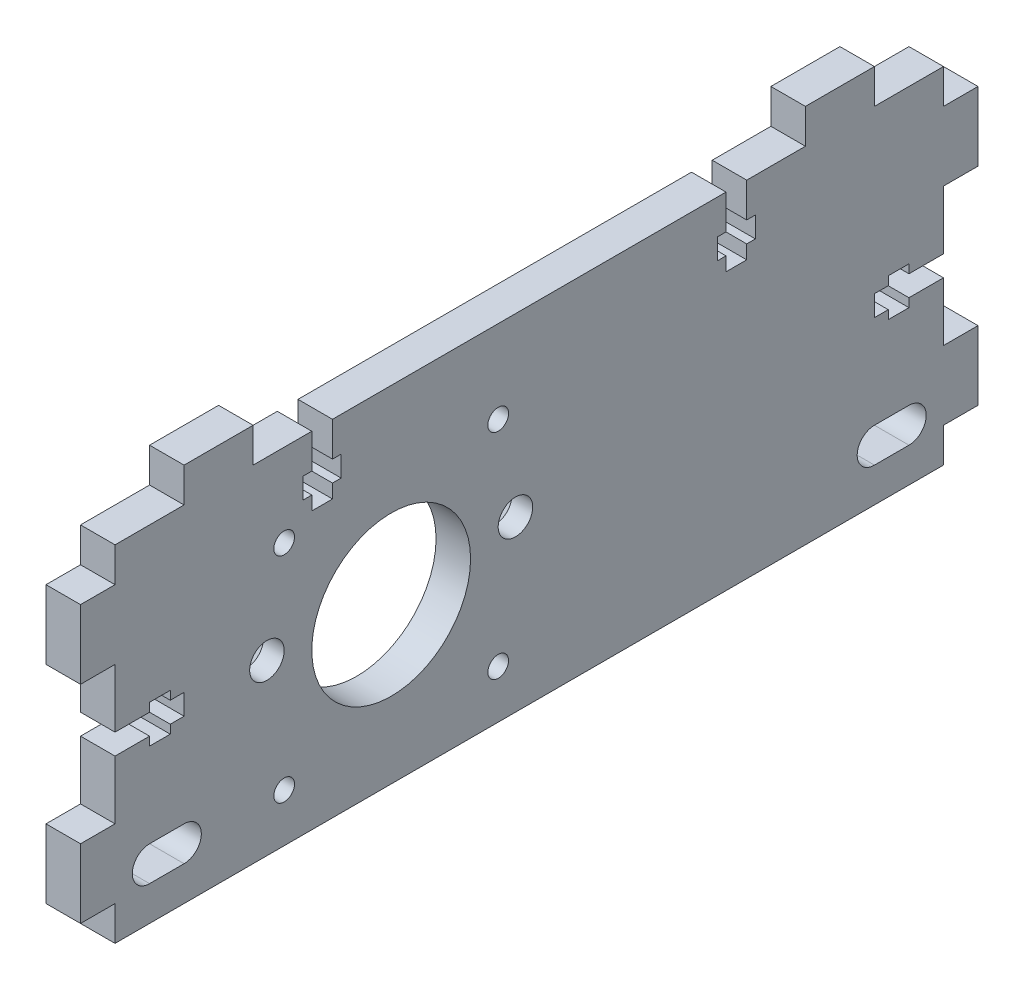
SolidWorks part; units mm, degrees
material "Maple"
ref_plane "Front Plane" through (0, 0, 0) normal (0, 0, 1) x (1, 0, 0)
ref_plane "Top Plane" through (0, 0, 0) normal (0, 1, 0) x (1, 0, 0)
ref_plane "Right Plane" through (0, 0, 0) normal (1, 0, 0) x (0, 0, -1)
sketch "Sketch1" plane through (0, 0, 0) normal (1, 0, 0) x (0, 0, -1)
  line L0 (-95.5, 38) -> (-64.5, 7) construction
  line L1 (-120, 50) -> (0, 50)
  line L2 (-120, 50) -> (-120, 0)
  line L3 (-120, 0) -> (0, 0)
  line L4 (0, 50) -> (0, 0)
  line L5 (-95.5, 38) -> (-64.5, 38) construction
  line L6 (-95.5, 38) -> (-95.5, 7) construction
  line L7 (-95.5, 7) -> (-64.5, 7) construction
  line L8 (-64.5, 38) -> (-64.5, 7) construction
  line L9 (-80, 22.5) -> (-80, 50) construction
  line L10 (-98, 24.5) -> (-80, 24.5) construction
  line L11 (-80, 24.5) -> (-62, 24.5) construction
  line L12 (-60, 50) -> (-60, 0) construction
  circle A0 centre (-95.5, 38) radius 1.5
  circle A1 centre (-64.5, 38) radius 1.5
  circle A2 centre (-64.5, 7) radius 1.5
  circle A3 centre (-95.5, 7) radius 1.5
  circle A4 centre (-80, 22.5) radius 11.5
  circle A5 centre (-98, 24.5) radius 2.5
  circle A6 centre (-62, 24.5) radius 2.5
  point P21 (-60, 50)
  dimension "D3" = 25.5
  dimension "D4" = 3
  dimension "D8" = 5
  dimension "D10" = 23
  dimension "D1" = 120
  dimension "D2" = 50
  dimension "D5" = 31
  dimension "D6" = 27.5
  dimension "D7" = 18
  dimension "D9" = 20
extrude "Boss-Extrude1" add sketch "Sketch1" along normal blind 5
chamfer "Chamfer1" distance 2 angle 45 2 edges at (0, 24.5, 95.5) (0, 24.5, 59.5)
sketch "Sketch2" plane through (5, 0, 0) normal (1, 0, 0) x (0, 0, -1)
  line L0 (-120, 50) -> (-120, 0) construction
  line L1 (-120, 5) -> (-125, 5)
  line L2 (-120, 5) -> (-120, 15)
  line L3 (-120, 15) -> (-125, 15)
  line L4 (-125, 5) -> (-125, 15)
  line L5 (-120, 45) -> (-125, 45)
  line L6 (-120, 45) -> (-120, 35)
  line L7 (-120, 35) -> (-125, 35)
  line L8 (-125, 45) -> (-125, 35)
  line L9 (0, 50) -> (-120, 50) construction
  line L10 (-110, 50) -> (-100, 50)
  line L11 (-110, 50) -> (-110, 55)
  line L12 (-110, 55) -> (-100, 55)
  line L13 (-100, 50) -> (-100, 55)
  line L14 (-60, 50) -> (-60, 0) construction
  line L15 (-120, 0) -> (0, 0) construction
  line L16 (-20, 50) -> (-20, 55)
  line L17 (-10, 55) -> (-20, 55)
  line L18 (-10, 50) -> (-10, 55)
  line L19 (-10, 50) -> (-20, 50)
  line L20 (5, 45) -> (5, 35)
  line L21 (0, 35) -> (5, 35)
  line L22 (0, 45) -> (0, 35)
  line L23 (0, 45) -> (5, 45)
  line L24 (5, 5) -> (5, 15)
  line L25 (0, 15) -> (5, 15)
  line L26 (0, 5) -> (0, 15)
  line L27 (0, 5) -> (5, 5)
  dimension "D1" = 5
  dimension "D2" = 10
  dimension "D3" = 10
  dimension "D4" = 10
  dimension "D5" = 10
  dimension "D6" = 5
  dimension "D7" = 5
extrude "Boss-Extrude2" add sketch "Sketch2" against normal up to surface (5 mm away) up to face at (0, 24.5, 93.5)
sketch "Sketch3" plane through (5, 0, 0) normal (1, 0, 0) x (0, 0, -1)
  line L0 (0, 26.5) -> (-5, 26.5)
  line L1 (-5, 26.5) -> (-5, 27.75)
  line L2 (-5, 27.75) -> (-8, 27.75)
  line L3 (-8, 27.75) -> (-8, 26.5)
  line L4 (-8, 26.5) -> (-10, 26.5)
  line L5 (-10, 26.5) -> (-10, 23.5)
  line L6 (-10, 23.5) -> (-8, 23.5)
  line L7 (-8, 23.5) -> (-8, 22.25)
  line L8 (-8, 22.25) -> (-5, 22.25)
  line L9 (-5, 22.25) -> (-5, 23.5)
  line L10 (-5, 23.5) -> (0, 23.5)
  line L11 (0, 23.5) -> (0, 26.5)
  line L12 (0, 15) -> (0, 35) construction
  line L13 (-60, 0) -> (-60, 50) construction
  line L14 (-120, 0) -> (0, 0) construction
  line L15 (-20, 50) -> (-100, 50) construction
  line L16 (-120, 23.5) -> (-120, 26.5)
  line L17 (-115, 23.5) -> (-120, 23.5)
  line L18 (-115, 22.25) -> (-115, 23.5)
  line L19 (-112, 22.25) -> (-115, 22.25)
  line L20 (-112, 23.5) -> (-112, 22.25)
  line L21 (-110, 23.5) -> (-112, 23.5)
  line L22 (-110, 26.5) -> (-110, 23.5)
  line L23 (-112, 26.5) -> (-110, 26.5)
  line L24 (-112, 27.75) -> (-112, 26.5)
  line L25 (-115, 27.75) -> (-112, 27.75)
  line L26 (-115, 26.5) -> (-115, 27.75)
  line L27 (-120, 26.5) -> (-115, 26.5)
  line L28 (-31.5, 50) -> (-31.5, 45)
  line L29 (-31.5, 45) -> (-32.75, 45)
  line L30 (-32.75, 45) -> (-32.75, 42)
  line L31 (-32.75, 42) -> (-31.5, 42)
  line L32 (-31.5, 42) -> (-31.5, 40)
  line L33 (-31.5, 40) -> (-28.5, 40)
  line L34 (-28.5, 40) -> (-28.5, 42)
  line L35 (-28.5, 42) -> (-27.25, 42)
  line L36 (-27.25, 42) -> (-27.25, 45)
  line L37 (-27.25, 45) -> (-28.5, 45)
  line L38 (-28.5, 45) -> (-28.5, 50)
  line L39 (-28.5, 50) -> (-31.5, 50)
  line L40 (-91.5, 50) -> (-88.5, 50)
  line L41 (-91.5, 45) -> (-91.5, 50)
  line L42 (-92.75, 45) -> (-91.5, 45)
  line L43 (-92.75, 42) -> (-92.75, 45)
  line L44 (-91.5, 42) -> (-92.75, 42)
  line L45 (-91.5, 40) -> (-91.5, 42)
  line L46 (-88.5, 40) -> (-91.5, 40)
  line L47 (-88.5, 42) -> (-88.5, 40)
  line L48 (-87.25, 42) -> (-88.5, 42)
  line L49 (-87.25, 45) -> (-87.25, 42)
  line L50 (-88.5, 45) -> (-87.25, 45)
  line L51 (-88.5, 50) -> (-88.5, 45)
  line L52 (-115, 7.5) -> (-110, 7.5) construction
  line L53 (-115, 10) -> (-110, 10)
  line L54 (-115, 5) -> (-110, 5)
  line L55 (-120, 5) -> (-120, 0) construction
  line L56 (-5, 7.5) -> (-10, 7.5) construction
  line L57 (-5, 10) -> (-10, 10)
  line L58 (-5, 5) -> (-10, 5)
  arc A0 (-115, 10) -> (-115, 5) centre (-115, 7.5) ccw
  arc A1 (-110, 5) -> (-110, 10) centre (-110, 7.5) ccw
  arc A2 (-5, 10) -> (-5, 5) centre (-5, 7.5) cw
  arc A3 (-10, 5) -> (-10, 10) centre (-10, 7.5) cw
  point P2 (0, 25)
  point P13 (-2.5, 23.5)
  point P36 (-30, 50)
  point P48 (-112.5, 7.5)
  point P53 (-117.5, 7.5)
  point P70 (-120, 2.5)
  point P73 (-7.5, 7.5)
  dimension "D1" = 3
  dimension "D2" = 3
  dimension "D3" = 2
  dimension "D4" = 5
  dimension "D5" = 5.5
  dimension "D6" = 5
  dimension "D7" = 5
  dimension "D8" = 5
  dimension "D9" = 5.5
  dimension "D10" = 3
  dimension "D11" = 30
  dimension "D12" = 5
  dimension "D13" = 2.5
extrude "Cut-Extrude1" cut sketch "Sketch3" against normal through all
